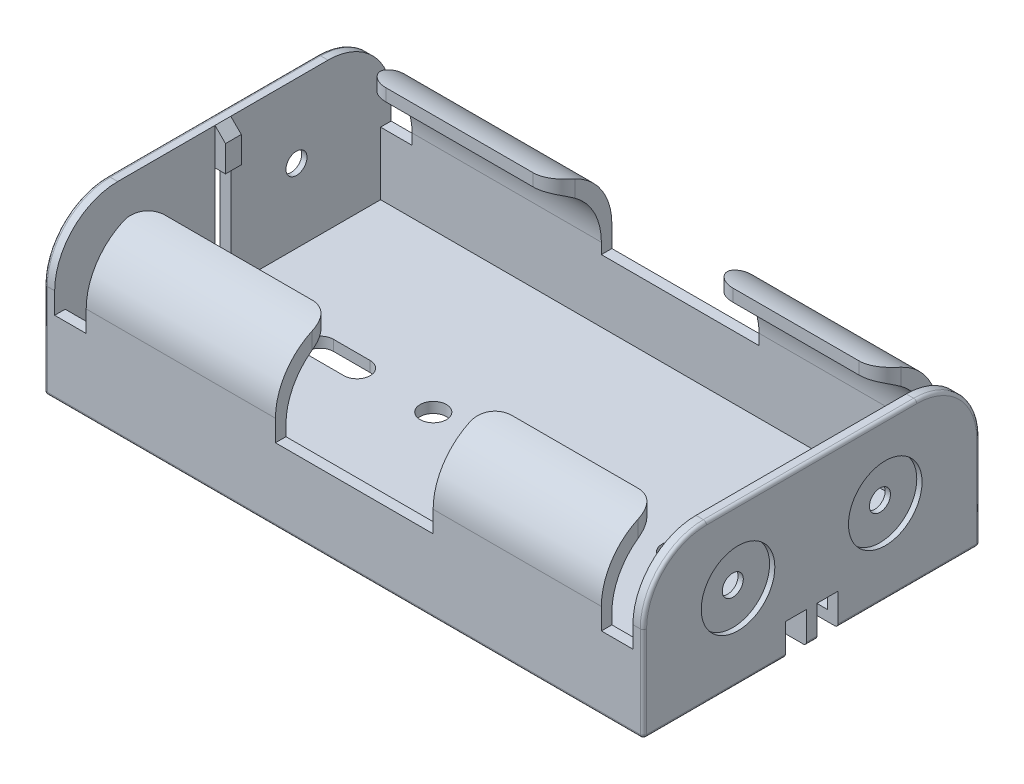
SolidWorks part; units mm, degrees
ref_plane "Front Plane" through (0, 0, 0) normal (0, 0, 1) x (1, 0, 0)
ref_plane "Top Plane" through (0, 0, 0) normal (0, 1, 0) x (1, 0, 0)
ref_plane "Right Plane" through (0, 0, 0) normal (1, 0, 0) x (0, 0, -1)
sketch "Sketch1" plane through (0, 0, 0) normal (1, 0, 0) x (0, 0, -1)
  line L1 (0, 0) -> (-32, 0)
  line L2 (0, 0) -> (0, 9)
  line L3 (-6, 15) -> (-26, 15)
  line L4 (-32, 0) -> (-32, 9)
  arc A0 (0, 9) -> (-6, 15) centre (-6, 9) ccw
  arc A1 (-26, 15) -> (-32, 9) centre (-26, 9) ccw
  point P7 (0, 15)
  point P10 (-32, 15)
  dimension "D3" = 6
  dimension "D1" = 32
  dimension "D2" = 15
extrude "Mechanical_Outline" add sketch "Sketch1" along normal blind 55
sketch "Sketch2" plane through (55, 0, 0) normal (1, 0, 0) x (0, 0, -1)
  line L0 (-32, 9) -> (-32, 0) construction
  line L1 (-25, 14) -> (-7, 14)
  line L2 (-31, 8) -> (-31, 1)
  line L3 (-31, 1) -> (-1, 1)
  line L4 (-1, 8) -> (-1, 1)
  line L6 (-32, 0) -> (0, 0) construction
  arc A0 (-7, 14) -> (-1, 8) centre (-7, 8) cw
  arc A1 (-25, 14) -> (-31, 8) centre (-25, 8) ccw
  point P10 (-1, 14)
  point P13 (-31, 14)
  dimension "D5" = 6
  dimension "D1" = 30
  dimension "D2" = 1
  dimension "D3" = 13
  dimension "D4" = 1
extrude "Cut-Extrude1" cut sketch "Sketch2" against normal up to next
sketch "Sketch3" plane through (0, 15, 0) normal (0, 1, 0) x (1, 0, 0)
  line L0 (0, -6) -> (0, -26) construction
  line L1 (0, -5.5) -> (55, -5.5)
  line L2 (0, -5.5) -> (0, -26.5)
  line L3 (0, -26.5) -> (55, -26.5)
  line L4 (55, -5.5) -> (55, -26.5)
  line L5 (55, -6) -> (55, -26) construction
  line L7 (0, -25) -> (0, -7) construction
  line L8 (55, -7) -> (55, -25) construction
  point P11 (55, -16)
  dimension "D1" = 21
  dimension "D2" = 10.5
extrude "Cut-Extrude2" cut sketch "Sketch3" against normal up to next
ref_plane "Plane1" through (0, 14.9791, 0) normal (0, 1, 0) x (1, 0, 0)
sketch "Sketch5" plane through (0, 14.9791, 0) normal (0, 1, 0) x (1, 0, 0)
  line L0 (55, -32) -> (0, -32) construction
  line L1 (0, 0) -> (3, 0)
  line L2 (0, 0) -> (0, -32)
  line L3 (0, -32) -> (3, -32)
  line L4 (3, 0) -> (3, -32)
  line L5 (55, 0) -> (0, 0) construction
  line L6 (21, 0) -> (36, 0)
  line L7 (21, 0) -> (21, -32)
  line L8 (21, -32) -> (36, -32)
  line L9 (36, 0) -> (36, -32)
  line L11 (55, 0) -> (52, 0)
  line L12 (55, 0) -> (55, -32)
  line L13 (55, -32) -> (52, -32)
  line L14 (52, 0) -> (52, -32)
  dimension "D1" = 3
  dimension "D2" = 3
  dimension "D3" = 15
  dimension "D4" = 21
extrude "Cut-Extrude3" cut sketch "Sketch5" against normal blind 8
sketch "Sketch6" plane through (55, 0, 0) normal (1, 0, 0) x (0, 0, -1)
  line L1 (-32, 0) -> (0, 0)
  line L2 (-32, 0) -> (-32, 9)
  line L3 (-26, 15) -> (-6, 15)
  line L4 (0, 0) -> (0, 9)
  arc A0 (-6, 15) -> (0, 9) centre (-6, 9) cw
  arc A1 (-32, 9) -> (-26, 15) centre (-26, 9) cw
  point P6 (0, 15)
  point P10 (-32, 15)
  dimension "D1" = 32
  dimension "D3" = 6
  dimension "D2" = 15
extrude "Boss-Extrude2" add sketch "Sketch6" along normal blind 1
sketch "Sketch7" plane through (0, 0, 0) normal (-1, 0, 0) x (0, 0, 1)
  line L1 (0, 0) -> (32, 0)
  line L2 (0, 0) -> (0, 9)
  line L3 (6, 15) -> (26, 15)
  line L4 (32, 0) -> (32, 9)
  arc A0 (26, 15) -> (32, 9) centre (26, 9) cw
  arc A1 (0, 9) -> (6, 15) centre (6, 9) cw
  point P6 (32, 15)
  point P11 (0, 15)
  dimension "D1" = 15
  dimension "D3" = 6
  dimension "D2" = 32
extrude "Boss-Extrude3" add sketch "Sketch7" along normal blind 1
sketch "Sketch8" plane through (-1, 0, 0) normal (-1, 0, 0) x (0, 0, 1)
  line L2 (0, 0) -> (32, 0) construction
  line L3 (32, 0) -> (32, 9) construction
  line L4 (0, 9) -> (0, 0) construction
  circle A0 centre (9, 8) radius 3.5
  circle A1 centre (23, 8) radius 3.5
  dimension "D2" = 7
  dimension "D3" = 7
  dimension "D4" = 8
  dimension "D5" = 9
  dimension "D6" = 9
  dimension "D1" = 14
extrude "Cut-Extrude4" cut sketch "Sketch8" against normal blind 0.5
sketch "Sketch9" plane through (-0.5, 0, 0) normal (-1, 0, 0) x (0, 0, 1)
  circle A0 centre (9, 8) radius 1
  circle A1 centre (23, 8) radius 1
  dimension "D1" = 2
  dimension "D2" = 2
extrude "Cut-Extrude5" cut sketch "Sketch9" against normal up to next
sketch "Sketch10" plane through (-1, 0, 0) normal (-1, 0, 0) x (0, 0, 1)
  line L0 (0, 9) -> (0, 0) construction
  line L1 (15.25, 11.5) -> (16.75, 11.5)
  line L2 (15.25, 11.5) -> (15.25, 3.5)
  line L3 (15.25, 3.5) -> (16.75, 3.5)
  line L4 (16.75, 11.5) -> (16.75, 3.5)
  line L7 (0, 0) -> (32, 0) construction
  dimension "D1" = 1.5
  dimension "D2" = 8
  dimension "D3" = 3.5
  dimension "D4" = 15.25
extrude "Cut-Extrude6" cut sketch "Sketch10" against normal up to next
sketch "Sketch11" plane through (0, 1, 0) normal (0, 1, 0) x (1, 0, 0)
  line L0 (9.25, -15.987) -> (12.75, -15.987) construction
  line L1 (9.25, -14.737) -> (12.75, -14.737)
  line L2 (9.25, -17.237) -> (12.75, -17.237)
  line L4 (-1, 0) -> (-1, -32) construction
  circle A0 centre (27, -16) radius 1.5
  circle A1 centre (20, -15.987) radius 1.25
  circle A2 centre (34, -16) radius 1.25
  circle A3 centre (43, -15.987) radius 1.25
  arc A4 (9.25, -14.737) -> (9.25, -17.237) centre (9.25, -15.987) ccw
  arc A5 (12.75, -17.237) -> (12.75, -14.737) centre (12.75, -15.987) ccw
  point P10 (11, -15.987)
  dimension "D1" = 3
  dimension "D2" = 2.5
  dimension "D3" = 2.5
  dimension "D4" = 2.5
  dimension "D6" = 3.5
  dimension "D9" = 7
  dimension "D10" = 7
  dimension "D11" = 9
  dimension "D5" = 2.5
  dimension "D7" = 12
  dimension "D8" = 9
extrude "Cut-Extrude7" cut sketch "Sketch11" against normal up to next
sketch "Sketch12" plane through (56, 0, 0) normal (1, 0, 0) x (0, 0, -1)
  line L2 (-32, 9) -> (-32, 0) construction
  line L3 (-32, 0) -> (0, 0) construction
  circle A0 centre (-23, 8) radius 3.5
  circle A1 centre (-9, 8) radius 3.5
  dimension "D2" = 9
  dimension "D3" = 8
  dimension "D4" = 8
  dimension "D5" = 7
  dimension "D6" = 7
  dimension "D1" = 14
extrude "Cut-Extrude8" cut sketch "Sketch12" against normal blind 0.5
sketch "Sketch13" plane through (55.5, 0, 0) normal (1, 0, 0) x (0, 0, -1)
  circle A0 centre (-23, 8) radius 1
  circle A1 centre (-9, 8) radius 1
  dimension "D1" = 2
  dimension "D2" = 2
extrude "Cut-Extrude9" cut sketch "Sketch13" against normal up to next
sketch "Sketch15" plane through (56, 0, 0) normal (1, 0, 0) x (0, 0, -1)
  line L1 (-18.5, 0) -> (-16.5, 0)
  line L2 (-18.5, 0) -> (-18.5, 3)
  line L3 (-18.5, 3) -> (-16.5, 3)
  line L4 (-16.5, 0) -> (-16.5, 3)
  line L5 (0, 0) -> (0, 9) construction
  line L6 (-15.5, 0) -> (-13.5, 0)
  line L7 (-15.5, 0) -> (-15.5, 3)
  line L8 (-15.5, 3) -> (-13.5, 3)
  line L9 (-13.5, 0) -> (-13.5, 3)
  line L12 (-6, 15) -> (-26, 15) construction
  dimension "D1" = 1
  dimension "D2" = 2
  dimension "D3" = 2
  dimension "D4" = 13.5
  dimension "D5" = 3
  dimension "D6" = 3
  dimension "D7" = 12
  dimension "D8" = 12
extrude "Cut-Extrude10" cut sketch "Sketch15" against normal blind 3
sketch "Sketch16" plane through (0, 0, 0) normal (0, -1, 0) x (1, 0, 0)
  line L1 (54, 25.5) -> (55, 25.5)
  line L2 (54, 25.5) -> (54, 20.5)
  line L3 (54, 20.5) -> (55, 20.5)
  line L4 (55, 25.5) -> (55, 20.5)
  line L5 (54, 11.5) -> (55, 11.5)
  line L6 (54, 11.5) -> (54, 6.5)
  line L7 (54, 6.5) -> (55, 6.5)
  line L8 (55, 11.5) -> (55, 6.5)
  line L11 (56, 32) -> (56, 18.5) construction
  line L12 (56, 13.5) -> (56, 0) construction
  line L13 (53, 18.5) -> (56, 18.5) construction
  line L14 (53, 13.5) -> (56, 13.5) construction
  dimension "D1" = 1
  dimension "D2" = 1
  dimension "D3" = 1
  dimension "D4" = 1
  dimension "D5" = 5
  dimension "D6" = 5
  dimension "D7" = 2
  dimension "D8" = 2
extrude "Cut-Extrude11" cut sketch "Sketch16" against normal up to next
sketch "Sketch17" plane through (0, 0, 0) normal (1, 0, 0) x (0, 0, -1)
  line L0 (-1, 1) -> (-31, 1) construction
  line L1 (-16.75, 3.5) -> (-15.25, 3.5)
  line L2 (-16.75, 3.5) -> (-16.75, 1)
  line L3 (-16.75, 1) -> (-15.25, 1)
  line L4 (-15.25, 3.5) -> (-15.25, 1)
extrude "Boss-Extrude4" add sketch "Sketch17" along normal blind 1
sketch "Sketch18" plane through (0, 0, 0) normal (1, 0, 0) x (0, 0, -1)
  line L1 (-16.75, 11.5) -> (-15.25, 11.5)
  line L2 (-16.75, 11.5) -> (-16.75, 15)
  line L3 (-16.75, 15) -> (-15.25, 15)
  line L4 (-15.25, 11.5) -> (-15.25, 15)
  dimension "D1" = 3.5
extrude "Boss-Extrude5" add sketch "Sketch18" along normal blind 1
chamfer "Chamfer1" distance 1 angle 45 1 edges at (1, 15, 16)
sketch "Sketch19" plane through (55, 0, 0) normal (-1, 0, 0) x (0, 0, 1)
  line L1 (15.5, 1) -> (16.5, 1)
  line L2 (15.5, 1) -> (15.5, 6)
  line L3 (15.5, 6) -> (16.5, 6)
  line L4 (16.5, 1) -> (16.5, 6)
  dimension "D1" = 5
extrude "Boss-Extrude6" add sketch "Sketch19" along normal blind 1
fillet "Fillet2" radius 2 8 edges at (52, 14.3943, 26.5) (36, 14.3943, 26.5) (21, 14.3943, 26.5) (3, 14.3943, 26.5) (3, 14.3943, 5.5) (21, 14.3943, 5.5) (36, 14.3943, 5.5) (52, 14.3943, 5.5)
fillet "Fillet3" radius 0.3 16 edges at (-1, 4.5, 32) (-1, 13.2426, 30.2426) (-1, 4.5, 0) (-1, 13.2426, 1.7574) (56, 4.5, 0) (56, 13.2426, 1.7574) (56, 4.5, 32) (56, 13.2426, 30.2426) (-1, 15, 16) (56, 0, 16) (56, 0, 6.75) (56, 0, 25.25) (27.5, 0, 32) (-1, 0, 16) (27.5, 0, 0) (56, 15, 16)
